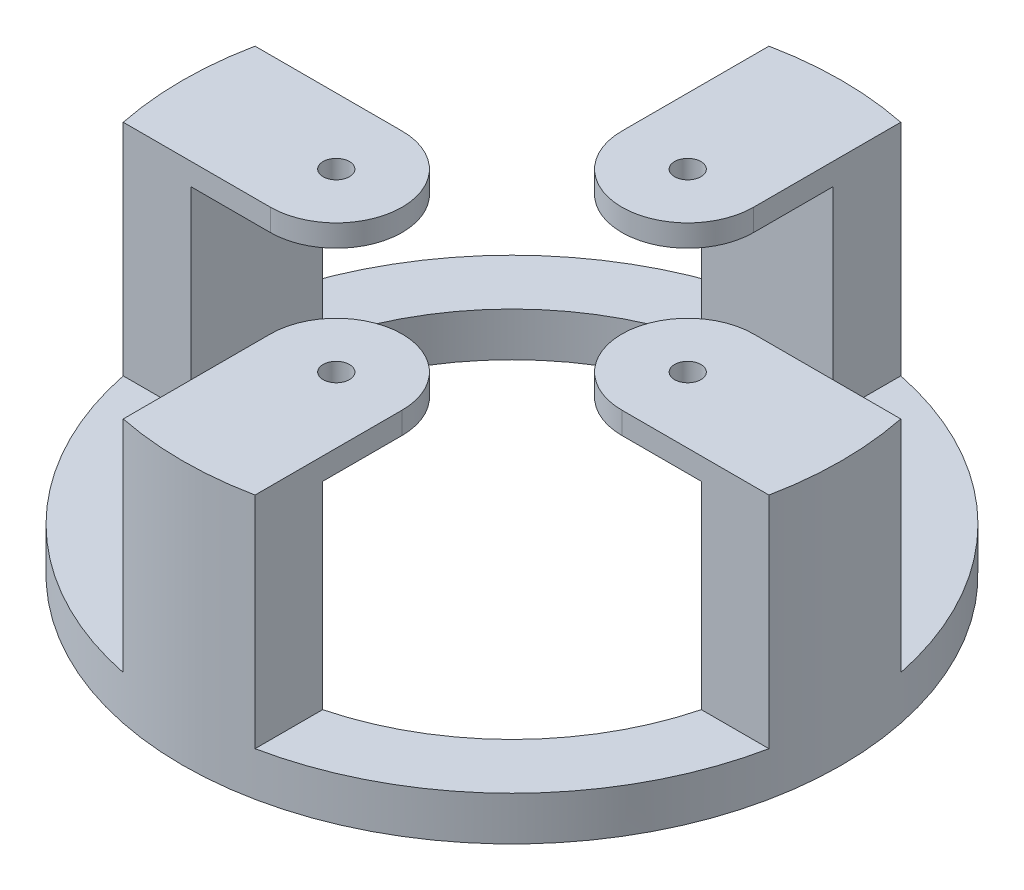
SolidWorks part; units mm, degrees
ref_plane "前视基准面" through (0, 0, 0) normal (0, 0, 1) x (1, 0, 0)
ref_plane "上视基准面" through (0, 0, 0) normal (0, 1, 0) x (1, 0, 0)
ref_plane "右视基准面" through (0, 0, 0) normal (1, 0, 0) x (0, 0, -1)
other "Configuration Table"
sketch "草图1" plane through (0, 0, 0) normal (0, 1, 0) x (1, 0, 0)
  circle A0 centre (0, 0) radius 75
  circle A1 centre (0, 0) radius 60
  dimension "D1" = 150
  dimension "D2" = 120
extrude "凸台-拉伸1" add sketch "草图1" along normal blind 10
sketch "草图2" plane through (0, 0, 0) normal (0, 1, 0) x (1, 0, 0)
  line L0 (-1000, 0) -> (49000, 0) construction
  line L1 (-707.1068, -707.1068) -> (34648.2323, 34648.2323) construction
  line L2 (-58.0948, -15) -> (-58.0948, 15)
  line L3 (-58.0948, 15) -> (-73.4847, 15)
  line L4 (-58.0948, -15) -> (-73.4847, -15)
  line L5 (-15, -58.0948) -> (-15, -73.4847)
  line L6 (-15, -58.0948) -> (15, -58.0948)
  line L7 (15, -58.0948) -> (15, -73.4847)
  line L8 (0, -1000) -> (0, 49000) construction
  line L9 (58.0948, -15) -> (58.0948, 15)
  line L10 (58.0948, -15) -> (73.4847, -15)
  line L11 (58.0948, 15) -> (73.4847, 15)
  line L12 (-15, 58.0948) -> (-15, 73.4847)
  line L13 (-15, 58.0948) -> (15, 58.0948)
  line L14 (15, 58.0948) -> (15, 73.4847)
  circle A0 centre (0, 0) radius 60 construction
  circle A1 centre (0, 0) radius 75 construction
  circle A2 centre (0, 0) radius 60 construction
  arc A3 (-73.4847, 15) -> (-73.4847, -15) centre (0, 0) ccw
  arc A4 (15, -73.4847) -> (-15, -73.4847) centre (0, 0) cw
  arc A5 (73.4847, 15) -> (73.4847, -15) centre (0, 0) cw
  arc A6 (15, 73.4847) -> (-15, 73.4847) centre (0, 0) ccw
  point P14 (-58.0948, 0)
  dimension "D1" = 30
extrude "凸台-拉伸2" add sketch "草图2" along normal blind 60 from surface at 0 starting at face at (0, 0, 75)
sketch "草图3" plane through (0, 0, 0) normal (0, 1, 0) x (1, 0, 0)
  line L0 (73.4847, 15) -> (58.0948, 15) construction
  line L2 (58.0948, -15) -> (73.4847, -15) construction
  line L6 (-73.4847, -15) -> (-58.0948, -15) construction
  line L8 (-58.0948, 15) -> (-73.4847, 15) construction
  line L12 (73.4847, 15) -> (58.0948, 15)
  line L14 (58.0948, -15) -> (73.4847, -15)
  line L18 (-73.4847, -15) -> (-58.0948, -15)
  line L20 (-58.0948, 15) -> (-73.4847, 15)
  line L24 (-40, 0) -> (40, 0) construction
  line L25 (-58.0948, 15) -> (-40, 15)
  line L26 (-58.0948, -15) -> (-40, -15)
  line L27 (58.0948, 15) -> (40, 15)
  line L28 (58.0948, -15) -> (40, -15)
  line L29 (-707.1068, -707.1068) -> (34648.2323, 34648.2323) construction
  line L30 (-15, 58.0948) -> (-15, 73.4847)
  line L31 (-15, 58.0948) -> (-15, 40)
  line L32 (15, 58.0948) -> (15, 40)
  line L33 (15, 73.4847) -> (15, 58.0948)
  line L34 (-15, -58.0948) -> (-15, -40)
  line L35 (-15, -73.4847) -> (-15, -58.0948)
  line L36 (15, -58.0948) -> (15, -40)
  line L37 (15, -58.0948) -> (15, -73.4847)
  arc A0 (73.4847, -15) -> (73.4847, 15) centre (0, 0) ccw construction
  arc A2 (-73.4847, 15) -> (-73.4847, -15) centre (0, 0) ccw construction
  arc A4 (73.4847, -15) -> (73.4847, 15) centre (0, 0) ccw
  arc A6 (-73.4847, 15) -> (-73.4847, -15) centre (0, 0) ccw
  arc A8 (-40, -15) -> (-40, 15) centre (-40, 0) ccw
  arc A9 (40, 15) -> (40, -15) centre (40, 0) ccw
  circle A10 centre (-40, 0) radius 3
  circle A11 centre (40, 0) radius 3
  circle A12 centre (0, 40) radius 3
  arc A13 (-15, 73.4847) -> (15, 73.4847) centre (0, 0) cw
  arc A14 (15, 40) -> (-15, 40) centre (0, 40) cw
  circle A15 centre (0, -40) radius 3
  arc A16 (15, -73.4847) -> (-15, -73.4847) centre (0, 0) cw
  arc A17 (-15, -40) -> (15, -40) centre (0, -40) cw
  point P8 (0, 0)
  dimension "D2" = 30
  dimension "D3" = 30
  dimension "D4" = 6
  dimension "D5" = 6
  dimension "D1" = 80
extrude "凸台-拉伸3" add sketch "草图3" against normal blind 5 from surface at 60 starting at face at (0, 60, 66.1685)
